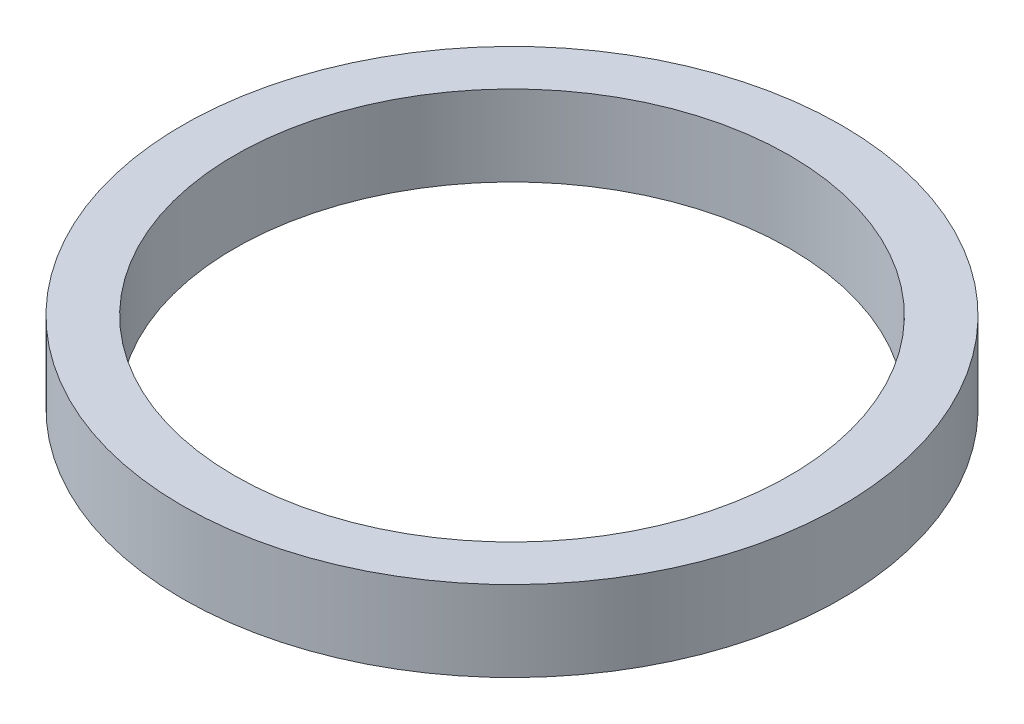
SolidWorks part; units mm, degrees
ref_plane "Plan de face" through (0, 0, 0) normal (0, 0, 1) x (1, 0, 0)
ref_plane "Plan de dessus" through (0, 0, 0) normal (0, 1, 0) x (1, 0, 0)
ref_plane "Plan de droite" through (0, 0, 0) normal (1, 0, 0) x (0, 0, -1)
sketch "Esquisse1" plane through (0, 0, 0) normal (0, 1, 0) x (1, 0, 0)
  circle A0 centre (0, 0) radius 17.225
  circle A1 centre (0, 0) radius 20.46
  dimension "D1" = 34.45
  dimension "D2" = 40.92
extrude "Boss.-Extru.1" add sketch "Esquisse1" along normal blind 5
